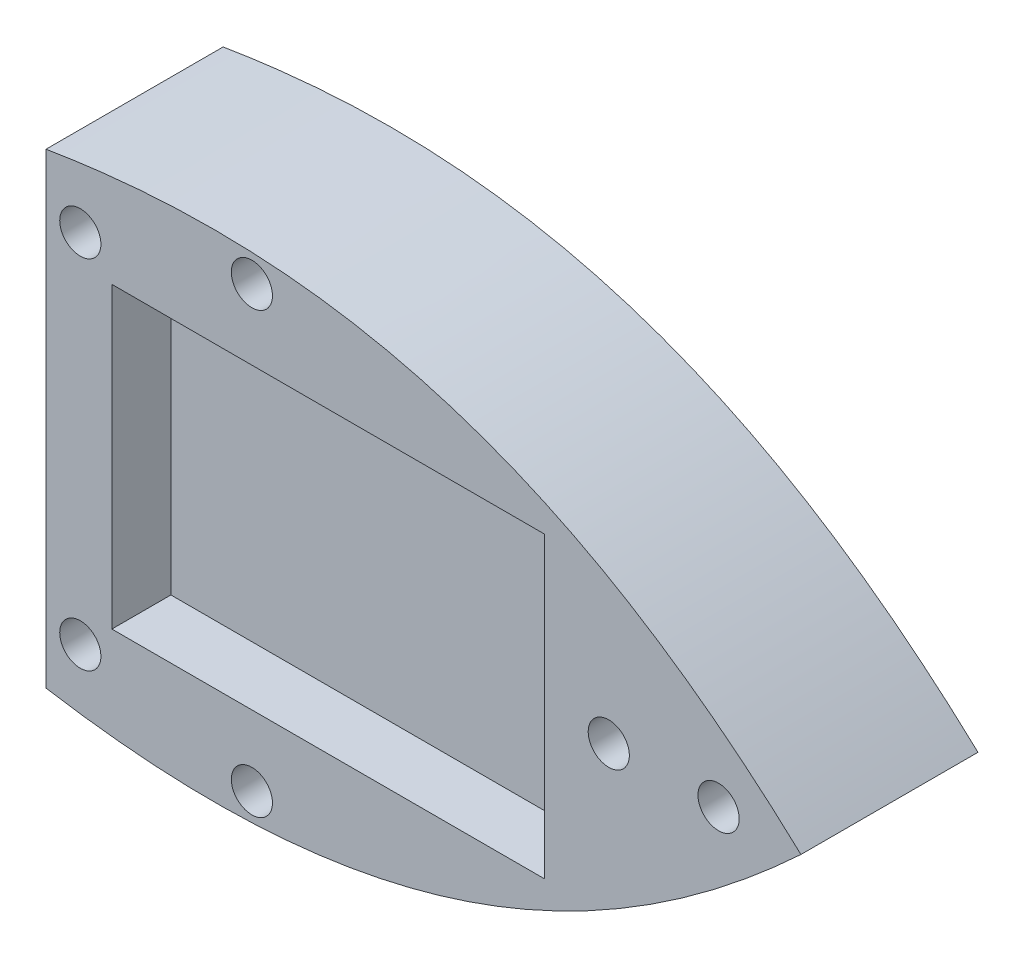
SolidWorks part; units mm, degrees
ref_plane "Front Plane" through (0, 0, 0) normal (0, 0, 1) x (1, 0, 0)
ref_plane "Top Plane" through (0, 0, 0) normal (0, 1, 0) x (1, 0, 0)
ref_plane "Right Plane" through (0, 0, 0) normal (1, 0, 0) x (0, 0, -1)
sketch "Sketch1" plane through (0, 0, 0) normal (0, 0, 1) x (1, 0, 0)
  line L0 (-12.5, 18) -> (-12.5, -18) construction
  line L1 (27.5, -18) -> (-27.5, -18) construction
  line L2 (27.5, -18) -> (27.5, 18) construction
  line L3 (27.5, 18) -> (-27.5, 18) construction
  line L4 (-27.5, -18) -> (-27.5, 18) construction
  line L5 (27.5, -18) -> (-27.5, 18) construction
  line L6 (27.5, 18) -> (-27.5, -18) construction
  line L7 (-25, 18) -> (-25, -18) construction
  line L8 (21.5, 18) -> (21.5, -18) construction
  line L9 (13.5, 18) -> (13.5, -18) construction
  line L10 (7.095, 0) -> (-7.095, 0) construction
  line L11 (-27.5, -17) -> (-27.5, 17)
  line L13 (8.8, -10.875) -> (-22.7, -10.875)
  line L14 (8.8, -10.875) -> (8.8, 10.875)
  line L15 (8.8, 10.875) -> (-22.7, 10.875)
  line L16 (-22.7, -10.875) -> (-22.7, 10.875)
  line L17 (8.8, -10.875) -> (-22.7, 10.875) construction
  line L18 (8.8, 10.875) -> (-22.7, -10.875) construction
  circle A0 centre (-25, 13) radius 1.5
  circle A1 centre (-12.5, 16) radius 1.5
  circle A2 centre (21.5, 0) radius 1.5
  circle A3 centre (13.5, 0) radius 1.5
  circle A6 centre (-12.5, -16) radius 1.5
  circle A7 centre (-25, -13) radius 1.5
  spline S0 degree 3 poles (-27.5, 17) (-7.1177, 20.3998) (10.5145, 15.8597) (27.5, 0) knots 0 0 0 0 1 1 1 1
  spline S1 degree 3 poles (-27.5, -17) (-7.1177, -20.3998) (10.5145, -15.8597) (27.5, 0) knots 0 0 0 0 1 1 1 1
  point P0 (0, 0)
  point P31 (-6.95, 0)
  point P39 (-27.5, 0)
  dimension "D7" = 3
  dimension "D8" = 5
  dimension "D1" = 36
  dimension "D2" = 55
  dimension "D3" = 15
  dimension "D4" = 2.5
  dimension "D5" = 6
  dimension "D6" = 14
  dimension "D9" = 2
  dimension "D10" = 17
  dimension "D11" = 31.5
  dimension "D12" = 4.8
  dimension "D13" = 21.75
extrude "Boss-Extrude2" add sketch "Sketch1" along normal blind 12.9
sketch "Sketch4" plane through (0, 0, 0) normal (0, 0, -1) x (-1, 0, 0)
  line L0 (22.7, -10.875) -> (-8.8, -10.875) construction
  line L1 (22.7, 10.875) -> (22.7, -10.875) construction
  line L2 (-8.8, 10.875) -> (22.7, 10.875) construction
  line L3 (-8.8, -10.875) -> (-8.8, 10.875) construction
  line L4 (22.7, -10.875) -> (-8.8, -10.875)
  line L5 (22.7, 10.875) -> (22.7, -10.875)
  line L6 (-8.8, 10.875) -> (22.7, 10.875)
  line L7 (-8.8, -10.875) -> (-8.8, 10.875)
extrude "Boss-Extrude3" add sketch "Sketch4" against normal blind 8.6
